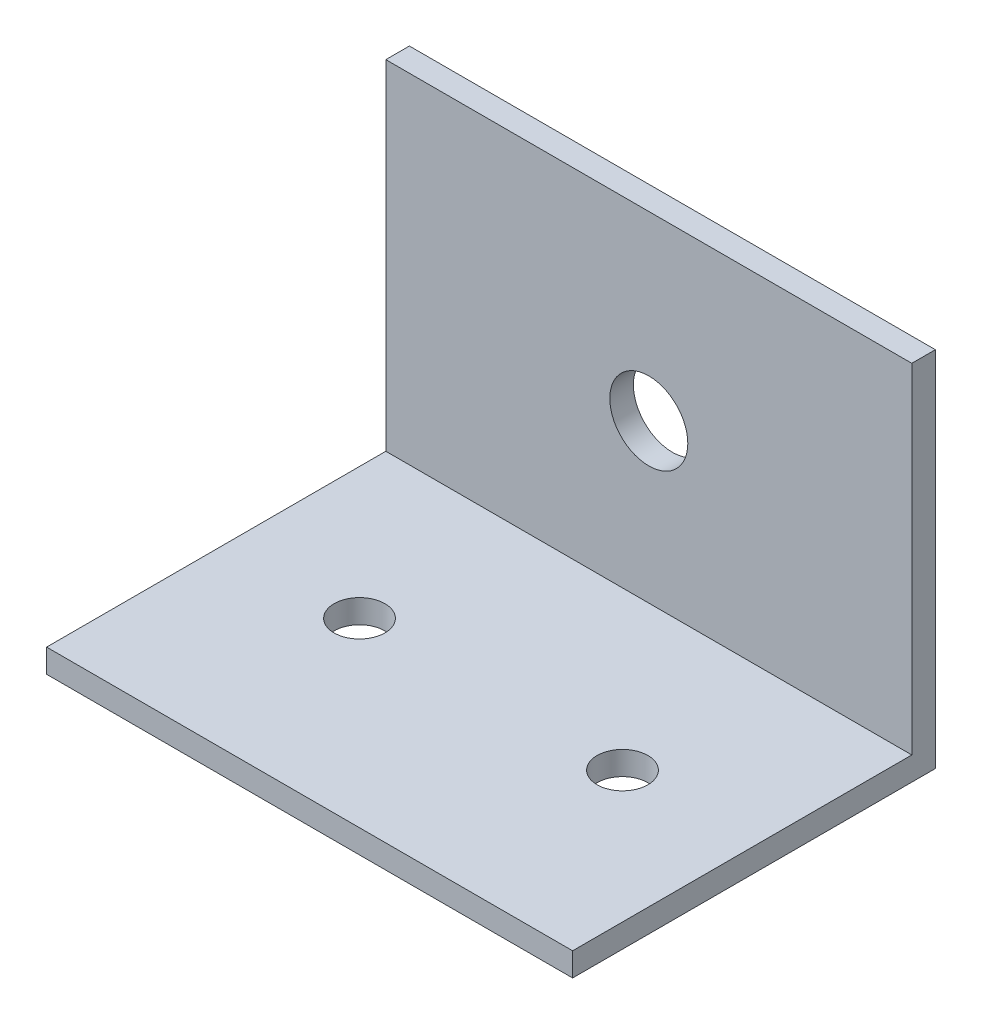
SolidWorks part; units mm, degrees
ref_plane "Front Plane" through (0, 0, 0) normal (0, 0, 1) x (1, 0, 0)
ref_plane "Top Plane" through (0, 0, 0) normal (0, 1, 0) x (1, 0, 0)
ref_plane "Right Plane" through (0, 0, 0) normal (1, 0, 0) x (0, 0, -1)
sketch "Sketch1" plane through (0, 0, 0) normal (0, 0, 1) x (1, 0, 0)
  line L1 (-36.83, 25.4) -> (36.83, 25.4)
  line L2 (-36.83, 25.4) -> (-36.83, -25.4)
  line L3 (-36.83, -25.4) -> (36.83, -25.4)
  line L4 (36.83, 25.4) -> (36.83, -25.4)
  line L5 (-36.83, 25.4) -> (36.83, -25.4) construction
  line L6 (-36.83, -25.4) -> (36.83, 25.4) construction
  point P0 (0, 0)
  dimension "D1" = 73.66
  dimension "D2" = 50.8
extrude "Boss-Extrude2" add sketch "Sketch1" along normal blind 3.302
sketch "Sketch4" plane through (0, 0, 3.302) normal (0, 0, 1) x (1, 0, 0)
  line L0 (36.83, -25.4) -> (36.83, 25.4) construction
  line L1 (-36.83, -25.4) -> (36.83, -25.4)
  line L2 (-36.83, -25.4) -> (-36.83, -22.098)
  line L3 (-36.83, -22.098) -> (36.83, -22.098)
  line L4 (36.83, -25.4) -> (36.83, -22.098)
  dimension "D1" = 3.302
extrude "Boss-Extrude3" add sketch "Sketch4" along normal blind 47.498
sketch "Sketch5" plane through (0, 0, 0) normal (0, 0, -1) x (-1, 0, 0)
  circle A0 centre (0, 0) radius 5.461
  dimension "D1" = 10.922
extrude "Cut-Extrude2" cut sketch "Sketch5" against normal through all contours A0
sketch "Sketch8" plane through (0, -25.4, 0) normal (0, -1, 0) x (1, 0, 0)
  circle A0 centre (-18.415, 25.4) radius 3.556
  circle A1 centre (18.415, 25.4) radius 3.556
  dimension "D1" = 7.112
  dimension "D2" = 7.112
extrude "Cut-Extrude3" cut sketch "Sketch8" against normal through all contours A0 | A1
